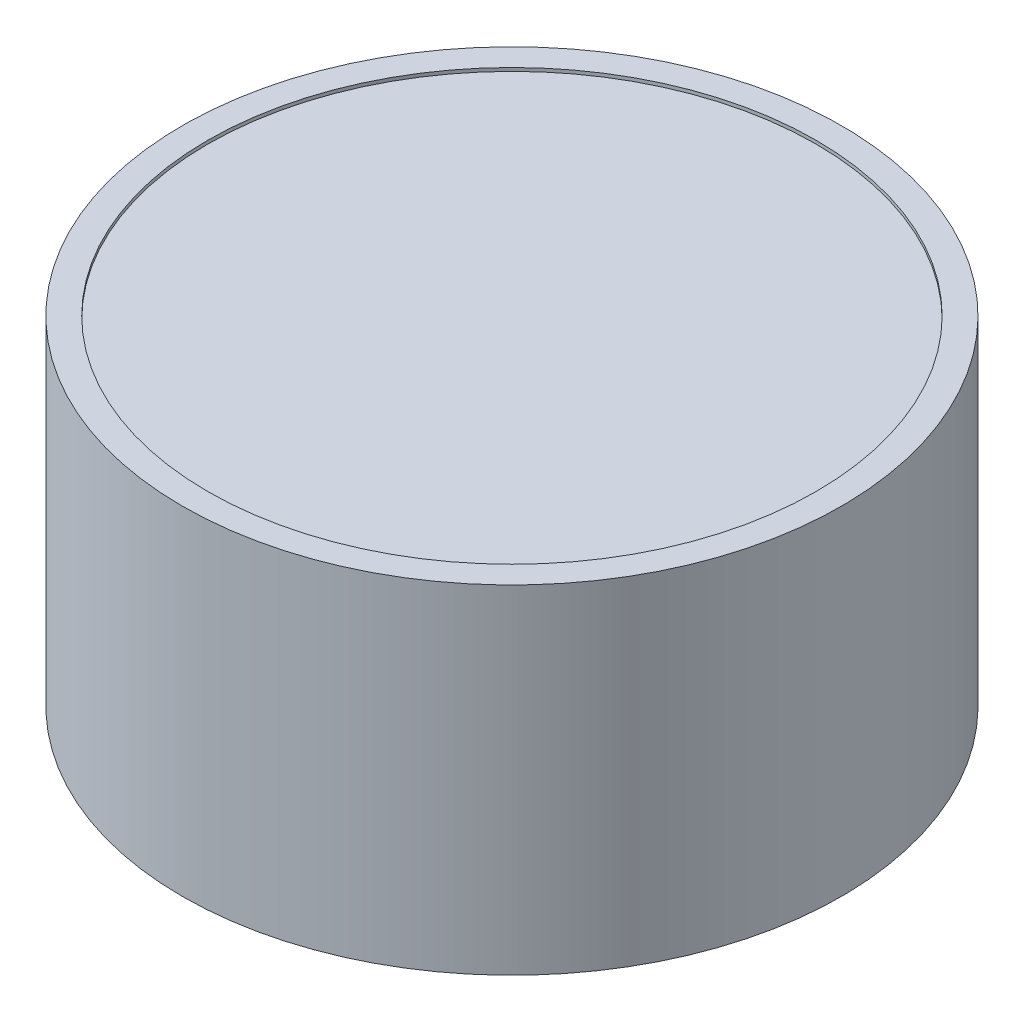
SolidWorks part; units mm, degrees
ref_plane "Front Plane" through (0, 0, 0) normal (0, 0, 1) x (1, 0, 0)
ref_plane "Top Plane" through (0, 0, 0) normal (0, 1, 0) x (1, 0, 0)
ref_plane "Right Plane" through (0, 0, 0) normal (1, 0, 0) x (0, 0, -1)
sketch "Sketch2" plane through (0, 0, 0) normal (0, 1, 0) x (1, 0, 0)
  circle A0 centre (0, 0) radius 4.875
  dimension "D1" = 9.75
extrude "Boss-Extrude1" add sketch "Sketch2" along normal blind 5
sketch "Sketch3" plane through (0, 5, 0) normal (0, 1, 0) x (1, 0, 0)
  circle A0 centre (0, 0) radius 4.5
  dimension "D1" = 9
extrude "Cut-Extrude1" cut sketch "Sketch3" against normal blind 1
sketch "Sketch4" plane through (0, 4, 0) normal (0, 1, 0) x (1, 0, 0)
  circle A1 centre (0, 0) radius 4.5
  circle A2 centre (0, 0) radius 4.5
  dimension "D1" = 0
extrude "Boss-Extrude2" add sketch "Sketch4" along normal blind 0.95
